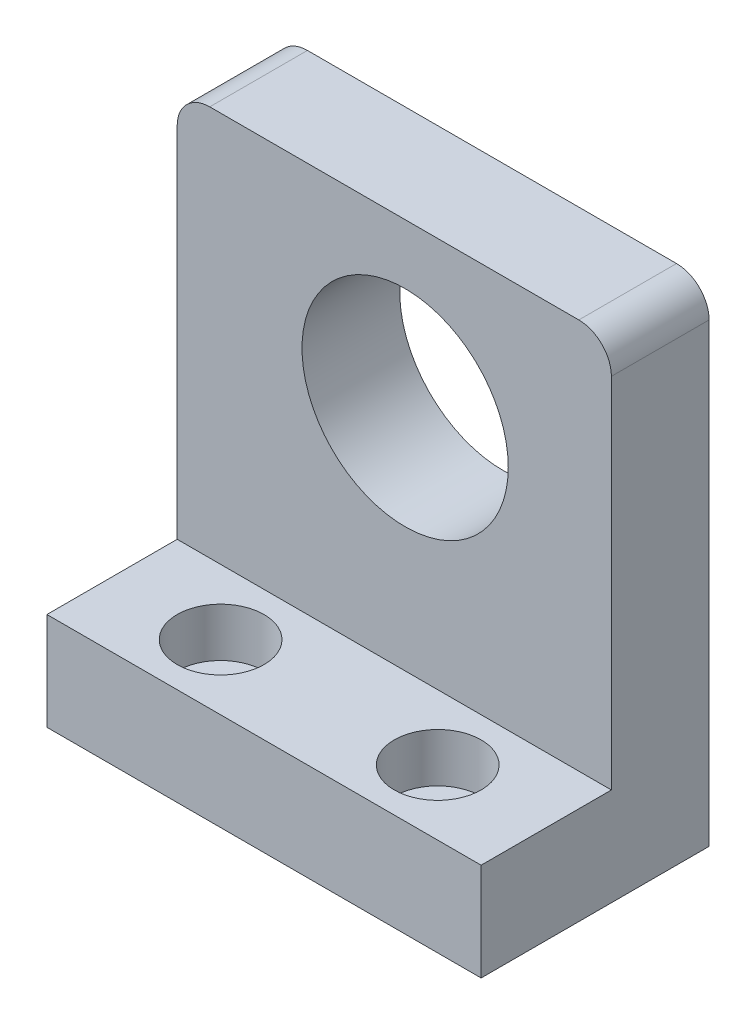
SolidWorks part; units mm, degrees
material "AISI 1035 Acero (SS)"
ref_plane "Alzado" through (0, 0, 0) normal (0, 0, 1) x (1, 0, 0)
ref_plane "Planta" through (0, 0, 0) normal (0, 1, 0) x (1, 0, 0)
ref_plane "Vista lateral" through (0, 0, 0) normal (1, 0, 0) x (0, 0, -1)
sketch "Croquis1" plane through (0, 0, 0) normal (0, 0, 1) x (1, 0, 0)
  line L1 (-17, 22.5) -> (17, 22.5)
  line L2 (-20, 19.5) -> (-20, -22.5)
  line L3 (-20, -22.5) -> (20, -22.5)
  line L4 (20, 19.5) -> (20, -22.5)
  line L5 (-20, 22.5) -> (20, -22.5) construction
  line L6 (-20, -22.5) -> (20, 22.5) construction
  arc A0 (17, 22.5) -> (20, 19.5) centre (17, 19.5) cw
  arc A1 (-17, 22.5) -> (-20, 19.5) centre (-17, 19.5) ccw
  circle A2 centre (1, 7.5) radius 9.5
  point P0 (0, 0)
  dimension "D3" = 3
  dimension "D4" = 15
  dimension "D5" = 19
  dimension "D1" = 45
  dimension "D2" = 40
extrude "Saliente-Extruir1" add sketch "Croquis1" along normal blind 9
sketch "Croquis3" plane through (0, 0, 9) normal (0, 0, 1) x (1, 0, 0)
  line L1 (-20, -22.5) -> (20, -22.5)
  line L2 (-20, -22.5) -> (-20, -13.5)
  line L3 (-20, -13.5) -> (20, -13.5)
  line L4 (20, -22.5) -> (20, -13.5)
  line L5 (20, -22.5) -> (20, 19.5) construction
  dimension "D1" = 9
  dimension "D2" = 40
extrude "Saliente-Extruir2" add sketch "Croquis3" along normal blind 12
sketch "Croquis4" plane through (0, -13.5, 0) normal (0, 1, 0) x (1, 0, 0)
  line L0 (-20, -21) -> (-20, -9) construction
  circle A0 centre (-10, -15) radius 2
  circle A1 centre (10, -15) radius 2
  dimension "D1" = 20
  dimension "D2" = 10
extrude "Cortar-Extruir1" cut sketch "Croquis4" against normal through all
sketch "Croquis5" plane through (0, -13.5, 0) normal (0, 1, 0) x (1, 0, 0)
  circle A0 centre (-10, -15) radius 4
  circle A1 centre (10, -15) radius 4
extrude "Cortar-Extruir2" cut sketch "Croquis5" against normal blind 4.5
